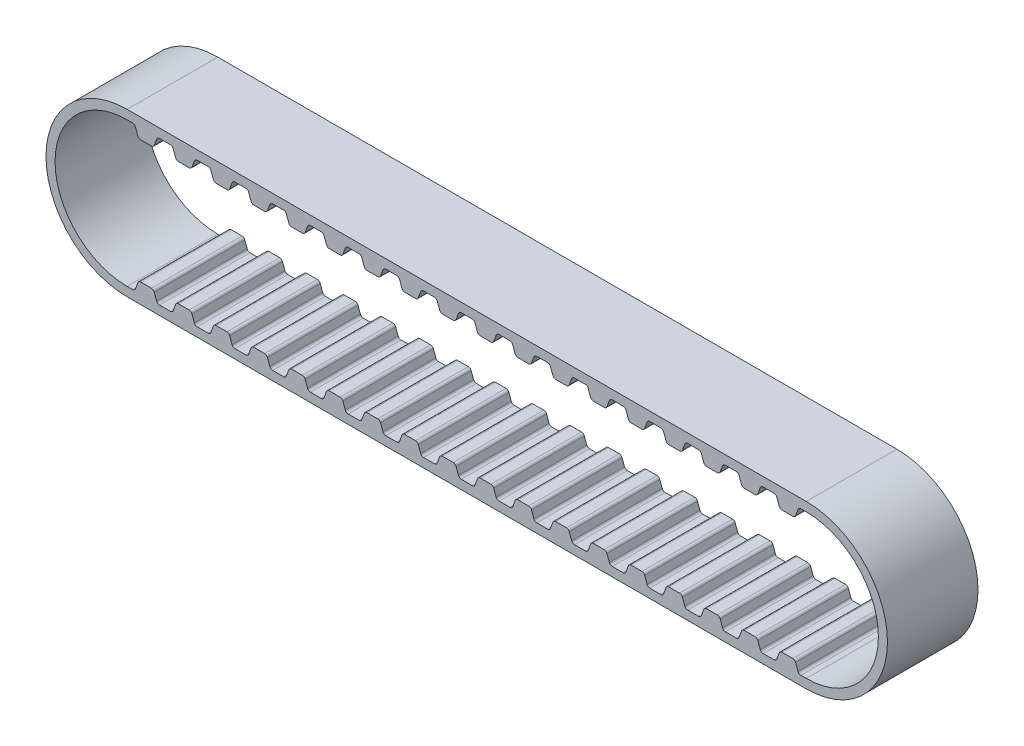
SolidWorks part; units mm, degrees
material "Gummi"
ref_plane "Ebene vorne" through (0, 0, 0) normal (0, 0, 1) x (1, 0, 0)
ref_plane "Ebene oben" through (0, 0, 0) normal (0, 1, 0) x (1, 0, 0)
ref_plane "Ebene rechts" through (0, 0, 0) normal (1, 0, 0) x (0, 0, -1)
sketch "Skizze1" plane through (0, 0, 0) normal (0, 0, 1) x (1, 0, 0)
  line L0 (0.7069, 1.1684) -> (0.5479, 0.7316)
  line L1 (0.36, 0.6) -> (0, 0.6)
  line L3 (0, 0) -> (45, 0)
  line L5 (21.9521, 0.7316) -> (21.7931, 1.1684)
  line L6 (11.9521, 0.7316) -> (11.7931, 1.1684)
  line L7 (11.6052, 1.3) -> (10.8948, 1.3)
  line L8 (10.7069, 1.1684) -> (10.5479, 0.7316)
  line L9 (10.36, 0.6) -> (9.64, 0.6)
  line L10 (9.4521, 0.7316) -> (9.2931, 1.1684)
  line L11 (9.1052, 1.3) -> (8.3948, 1.3)
  line L12 (8.2069, 1.1684) -> (8.0479, 0.7316)
  line L13 (7.86, 0.6) -> (7.14, 0.6)
  line L14 (6.9521, 0.7316) -> (6.7931, 1.1684)
  line L15 (6.6052, 1.3) -> (5.8948, 1.3)
  line L16 (5.7069, 1.1684) -> (5.5479, 0.7316)
  line L17 (5.36, 0.6) -> (4.64, 0.6)
  line L18 (4.4521, 0.7316) -> (4.2931, 1.1684)
  line L19 (4.1052, 1.3) -> (3.3948, 1.3)
  line L20 (3.2069, 1.1684) -> (3.0479, 0.7316)
  line L21 (2.86, 0.6) -> (2.14, 0.6)
  line L22 (1.9521, 0.7316) -> (1.7931, 1.1684)
  line L23 (1.6052, 1.3) -> (0.8948, 1.3)
  line L24 (21.6052, 1.3) -> (20.8948, 1.3)
  line L25 (20.7069, 1.1684) -> (20.5479, 0.7316)
  line L26 (20.36, 0.6) -> (19.64, 0.6)
  line L27 (19.4521, 0.7316) -> (19.2931, 1.1684)
  line L28 (19.1052, 1.3) -> (18.3948, 1.3)
  line L29 (18.2069, 1.1684) -> (18.0479, 0.7316)
  line L30 (17.86, 0.6) -> (17.14, 0.6)
  line L31 (16.9521, 0.7316) -> (16.7931, 1.1684)
  line L32 (16.6052, 1.3) -> (15.8948, 1.3)
  line L33 (15.7069, 1.1684) -> (15.5479, 0.7316)
  line L34 (15.36, 0.6) -> (14.64, 0.6)
  line L35 (14.4521, 0.7316) -> (14.2931, 1.1684)
  line L36 (14.1052, 1.3) -> (13.3948, 1.3)
  line L37 (13.2069, 1.1684) -> (13.0479, 0.7316)
  line L38 (12.86, 0.6) -> (12.14, 0.6)
  line L39 (31.9521, 0.7316) -> (31.7931, 1.1684)
  line L40 (31.6052, 1.3) -> (30.8948, 1.3)
  line L41 (30.7069, 1.1684) -> (30.5479, 0.7316)
  line L42 (30.36, 0.6) -> (29.64, 0.6)
  line L43 (29.4521, 0.7316) -> (29.2931, 1.1684)
  line L44 (29.1052, 1.3) -> (28.3948, 1.3)
  line L45 (28.2069, 1.1684) -> (28.0479, 0.7316)
  line L46 (27.86, 0.6) -> (27.14, 0.6)
  line L47 (26.9521, 0.7316) -> (26.7931, 1.1684)
  line L48 (26.6052, 1.3) -> (25.8948, 1.3)
  line L49 (25.7069, 1.1684) -> (25.5479, 0.7316)
  line L50 (25.36, 0.6) -> (24.64, 0.6)
  line L51 (24.4521, 0.7316) -> (24.2931, 1.1684)
  line L52 (24.1052, 1.3) -> (23.3948, 1.3)
  line L53 (23.2069, 1.1684) -> (23.0479, 0.7316)
  line L54 (22.86, 0.6) -> (22.14, 0.6)
  line L55 (41.9521, 0.7316) -> (41.7931, 1.1684)
  line L56 (41.6052, 1.3) -> (40.8948, 1.3)
  line L57 (40.7069, 1.1684) -> (40.5479, 0.7316)
  line L58 (40.36, 0.6) -> (39.64, 0.6)
  line L59 (39.4521, 0.7316) -> (39.2931, 1.1684)
  line L60 (39.1052, 1.3) -> (38.3948, 1.3)
  line L61 (38.2069, 1.1684) -> (38.0479, 0.7316)
  line L62 (37.86, 0.6) -> (37.14, 0.6)
  line L63 (36.9521, 0.7316) -> (36.7931, 1.1684)
  line L64 (36.6052, 1.3) -> (35.8948, 1.3)
  line L65 (35.7069, 1.1684) -> (35.5479, 0.7316)
  line L66 (35.36, 0.6) -> (34.64, 0.6)
  line L67 (34.4521, 0.7316) -> (34.2931, 1.1684)
  line L68 (34.1052, 1.3) -> (33.3948, 1.3)
  line L69 (33.2069, 1.1684) -> (33.0479, 0.7316)
  line L70 (32.86, 0.6) -> (32.14, 0.6)
  line L71 (44.4521, 0.7316) -> (44.2931, 1.1684)
  line L72 (44.1052, 1.3) -> (43.3948, 1.3)
  line L73 (43.2069, 1.1684) -> (43.0479, 0.7316)
  line L74 (42.86, 0.6) -> (42.14, 0.6)
  line L75 (44.64, 0.6) -> (45, 0.6)
  line L76 (45, 0.6) -> (45, 8.7132) construction
  line L80 (0, 10.76) -> (45, 10.76)
  line L153 (44.64, 10.16) -> (45, 10.16)
  line L154 (42.86, 10.16) -> (42.14, 10.16)
  line L155 (43.2069, 9.5916) -> (43.0479, 10.0284)
  line L156 (44.1052, 9.46) -> (43.3948, 9.46)
  line L157 (44.4521, 10.0284) -> (44.2931, 9.5916)
  line L158 (32.86, 10.16) -> (32.14, 10.16)
  line L159 (33.2069, 9.5916) -> (33.0479, 10.0284)
  line L160 (34.1052, 9.46) -> (33.3948, 9.46)
  line L161 (34.4521, 10.0284) -> (34.2931, 9.5916)
  line L162 (35.36, 10.16) -> (34.64, 10.16)
  line L163 (35.7069, 9.5916) -> (35.5479, 10.0284)
  line L164 (36.6052, 9.46) -> (35.8948, 9.46)
  line L165 (36.9521, 10.0284) -> (36.7931, 9.5916)
  line L166 (37.86, 10.16) -> (37.14, 10.16)
  line L167 (38.2069, 9.5916) -> (38.0479, 10.0284)
  line L168 (39.1052, 9.46) -> (38.3948, 9.46)
  line L169 (39.4521, 10.0284) -> (39.2931, 9.5916)
  line L170 (40.36, 10.16) -> (39.64, 10.16)
  line L171 (40.7069, 9.5916) -> (40.5479, 10.0284)
  line L172 (41.6052, 9.46) -> (40.8948, 9.46)
  line L173 (41.9521, 10.0284) -> (41.7931, 9.5916)
  line L174 (22.86, 10.16) -> (22.14, 10.16)
  line L175 (23.2069, 9.5916) -> (23.0479, 10.0284)
  line L176 (24.1052, 9.46) -> (23.3948, 9.46)
  line L177 (24.4521, 10.0284) -> (24.2931, 9.5916)
  line L178 (25.36, 10.16) -> (24.64, 10.16)
  line L179 (25.7069, 9.5916) -> (25.5479, 10.0284)
  line L180 (26.6052, 9.46) -> (25.8948, 9.46)
  line L181 (26.9521, 10.0284) -> (26.7931, 9.5916)
  line L182 (27.86, 10.16) -> (27.14, 10.16)
  line L183 (28.2069, 9.5916) -> (28.0479, 10.0284)
  line L184 (29.1052, 9.46) -> (28.3948, 9.46)
  line L185 (29.4521, 10.0284) -> (29.2931, 9.5916)
  line L186 (30.36, 10.16) -> (29.64, 10.16)
  line L187 (30.7069, 9.5916) -> (30.5479, 10.0284)
  line L188 (31.6052, 9.46) -> (30.8948, 9.46)
  line L189 (31.9521, 10.0284) -> (31.7931, 9.5916)
  line L190 (12.86, 10.16) -> (12.14, 10.16)
  line L191 (13.2069, 9.5916) -> (13.0479, 10.0284)
  line L192 (14.1052, 9.46) -> (13.3948, 9.46)
  line L193 (14.4521, 10.0284) -> (14.2931, 9.5916)
  line L194 (15.36, 10.16) -> (14.64, 10.16)
  line L195 (15.7069, 9.5916) -> (15.5479, 10.0284)
  line L196 (16.6052, 9.46) -> (15.8948, 9.46)
  line L197 (16.9521, 10.0284) -> (16.7931, 9.5916)
  line L198 (17.86, 10.16) -> (17.14, 10.16)
  line L199 (18.2069, 9.5916) -> (18.0479, 10.0284)
  line L200 (19.1052, 9.46) -> (18.3948, 9.46)
  line L201 (19.4521, 10.0284) -> (19.2931, 9.5916)
  line L202 (20.36, 10.16) -> (19.64, 10.16)
  line L203 (20.7069, 9.5916) -> (20.5479, 10.0284)
  line L204 (21.6052, 9.46) -> (20.8948, 9.46)
  line L205 (1.6052, 9.46) -> (0.8948, 9.46)
  line L206 (1.9521, 10.0284) -> (1.7931, 9.5916)
  line L207 (2.86, 10.16) -> (2.14, 10.16)
  line L208 (3.2069, 9.5916) -> (3.0479, 10.0284)
  line L209 (4.1052, 9.46) -> (3.3948, 9.46)
  line L210 (4.4521, 10.0284) -> (4.2931, 9.5916)
  line L211 (5.36, 10.16) -> (4.64, 10.16)
  line L212 (5.7069, 9.5916) -> (5.5479, 10.0284)
  line L213 (6.6052, 9.46) -> (5.8948, 9.46)
  line L214 (6.9521, 10.0284) -> (6.7931, 9.5916)
  line L215 (7.86, 10.16) -> (7.14, 10.16)
  line L216 (8.2069, 9.5916) -> (8.0479, 10.0284)
  line L217 (9.1052, 9.46) -> (8.3948, 9.46)
  line L218 (9.4521, 10.0284) -> (9.2931, 9.5916)
  line L219 (10.36, 10.16) -> (9.64, 10.16)
  line L220 (10.7069, 9.5916) -> (10.5479, 10.0284)
  line L221 (11.6052, 9.46) -> (10.8948, 9.46)
  line L222 (11.9521, 10.0284) -> (11.7931, 9.5916)
  line L223 (21.9521, 10.0284) -> (21.7931, 9.5916)
  line L226 (0.36, 10.16) -> (0, 10.16)
  line L227 (0.7069, 9.5916) -> (0.5479, 10.0284)
  line L228 (45, 8.7132) -> (45, 14.9063) construction
  line L229 (0, 0) -> (0, 10.76) construction
  arc A0 (0.5479, 0.7316) -> (0.36, 0.6) centre (0.36, 0.8) cw
  arc A1 (12.14, 0.6) -> (11.9521, 0.7316) centre (12.14, 0.8) cw
  arc A2 (11.7931, 1.1684) -> (11.6052, 1.3) centre (11.6052, 1.1) ccw
  arc A3 (10.8948, 1.3) -> (10.7069, 1.1684) centre (10.8948, 1.1) ccw
  arc A4 (10.5479, 0.7316) -> (10.36, 0.6) centre (10.36, 0.8) cw
  arc A5 (9.64, 0.6) -> (9.4521, 0.7316) centre (9.64, 0.8) cw
  arc A6 (9.2931, 1.1684) -> (9.1052, 1.3) centre (9.1052, 1.1) ccw
  arc A7 (8.3948, 1.3) -> (8.2069, 1.1684) centre (8.3948, 1.1) ccw
  arc A8 (8.0479, 0.7316) -> (7.86, 0.6) centre (7.86, 0.8) cw
  arc A9 (7.14, 0.6) -> (6.9521, 0.7316) centre (7.14, 0.8) cw
  arc A10 (6.7931, 1.1684) -> (6.6052, 1.3) centre (6.6052, 1.1) ccw
  arc A11 (5.8948, 1.3) -> (5.7069, 1.1684) centre (5.8948, 1.1) ccw
  arc A12 (5.5479, 0.7316) -> (5.36, 0.6) centre (5.36, 0.8) cw
  arc A13 (4.64, 0.6) -> (4.4521, 0.7316) centre (4.64, 0.8) cw
  arc A14 (4.2931, 1.1684) -> (4.1052, 1.3) centre (4.1052, 1.1) ccw
  arc A15 (3.3948, 1.3) -> (3.2069, 1.1684) centre (3.3948, 1.1) ccw
  arc A16 (3.0479, 0.7316) -> (2.86, 0.6) centre (2.86, 0.8) cw
  arc A17 (2.14, 0.6) -> (1.9521, 0.7316) centre (2.14, 0.8) cw
  arc A18 (1.7931, 1.1684) -> (1.6052, 1.3) centre (1.6052, 1.1) ccw
  arc A19 (0.8948, 1.3) -> (0.7069, 1.1684) centre (0.8948, 1.1) ccw
  arc A20 (22.14, 0.6) -> (21.9521, 0.7316) centre (22.14, 0.8) cw
  arc A21 (21.7931, 1.1684) -> (21.6052, 1.3) centre (21.6052, 1.1) ccw
  arc A22 (20.8948, 1.3) -> (20.7069, 1.1684) centre (20.8948, 1.1) ccw
  arc A23 (20.5479, 0.7316) -> (20.36, 0.6) centre (20.36, 0.8) cw
  arc A24 (19.64, 0.6) -> (19.4521, 0.7316) centre (19.64, 0.8) cw
  arc A25 (19.2931, 1.1684) -> (19.1052, 1.3) centre (19.1052, 1.1) ccw
  arc A26 (18.3948, 1.3) -> (18.2069, 1.1684) centre (18.3948, 1.1) ccw
  arc A27 (18.0479, 0.7316) -> (17.86, 0.6) centre (17.86, 0.8) cw
  arc A28 (17.14, 0.6) -> (16.9521, 0.7316) centre (17.14, 0.8) cw
  arc A29 (16.7931, 1.1684) -> (16.6052, 1.3) centre (16.6052, 1.1) ccw
  arc A30 (15.8948, 1.3) -> (15.7069, 1.1684) centre (15.8948, 1.1) ccw
  arc A31 (15.5479, 0.7316) -> (15.36, 0.6) centre (15.36, 0.8) cw
  arc A32 (14.64, 0.6) -> (14.4521, 0.7316) centre (14.64, 0.8) cw
  arc A33 (14.2931, 1.1684) -> (14.1052, 1.3) centre (14.1052, 1.1) ccw
  arc A34 (13.3948, 1.3) -> (13.2069, 1.1684) centre (13.3948, 1.1) ccw
  arc A35 (13.0479, 0.7316) -> (12.86, 0.6) centre (12.86, 0.8) cw
  arc A36 (32.14, 0.6) -> (31.9521, 0.7316) centre (32.14, 0.8) cw
  arc A37 (31.7931, 1.1684) -> (31.6052, 1.3) centre (31.6052, 1.1) ccw
  arc A38 (30.8948, 1.3) -> (30.7069, 1.1684) centre (30.8948, 1.1) ccw
  arc A39 (30.5479, 0.7316) -> (30.36, 0.6) centre (30.36, 0.8) cw
  arc A40 (29.64, 0.6) -> (29.4521, 0.7316) centre (29.64, 0.8) cw
  arc A41 (29.2931, 1.1684) -> (29.1052, 1.3) centre (29.1052, 1.1) ccw
  arc A42 (28.3948, 1.3) -> (28.2069, 1.1684) centre (28.3948, 1.1) ccw
  arc A43 (28.0479, 0.7316) -> (27.86, 0.6) centre (27.86, 0.8) cw
  arc A44 (27.14, 0.6) -> (26.9521, 0.7316) centre (27.14, 0.8) cw
  arc A45 (26.7931, 1.1684) -> (26.6052, 1.3) centre (26.6052, 1.1) ccw
  arc A46 (25.8948, 1.3) -> (25.7069, 1.1684) centre (25.8948, 1.1) ccw
  arc A47 (25.5479, 0.7316) -> (25.36, 0.6) centre (25.36, 0.8) cw
  arc A48 (24.64, 0.6) -> (24.4521, 0.7316) centre (24.64, 0.8) cw
  arc A49 (24.2931, 1.1684) -> (24.1052, 1.3) centre (24.1052, 1.1) ccw
  arc A50 (23.3948, 1.3) -> (23.2069, 1.1684) centre (23.3948, 1.1) ccw
  arc A51 (23.0479, 0.7316) -> (22.86, 0.6) centre (22.86, 0.8) cw
  arc A52 (42.14, 0.6) -> (41.9521, 0.7316) centre (42.14, 0.8) cw
  arc A53 (41.7931, 1.1684) -> (41.6052, 1.3) centre (41.6052, 1.1) ccw
  arc A54 (40.8948, 1.3) -> (40.7069, 1.1684) centre (40.8948, 1.1) ccw
  arc A55 (40.5479, 0.7316) -> (40.36, 0.6) centre (40.36, 0.8) cw
  arc A56 (39.64, 0.6) -> (39.4521, 0.7316) centre (39.64, 0.8) cw
  arc A57 (39.2931, 1.1684) -> (39.1052, 1.3) centre (39.1052, 1.1) ccw
  arc A58 (38.3948, 1.3) -> (38.2069, 1.1684) centre (38.3948, 1.1) ccw
  arc A59 (38.0479, 0.7316) -> (37.86, 0.6) centre (37.86, 0.8) cw
  arc A60 (37.14, 0.6) -> (36.9521, 0.7316) centre (37.14, 0.8) cw
  arc A61 (36.7931, 1.1684) -> (36.6052, 1.3) centre (36.6052, 1.1) ccw
  arc A62 (35.8948, 1.3) -> (35.7069, 1.1684) centre (35.8948, 1.1) ccw
  arc A63 (35.5479, 0.7316) -> (35.36, 0.6) centre (35.36, 0.8) cw
  arc A64 (34.64, 0.6) -> (34.4521, 0.7316) centre (34.64, 0.8) cw
  arc A65 (34.2931, 1.1684) -> (34.1052, 1.3) centre (34.1052, 1.1) ccw
  arc A66 (33.3948, 1.3) -> (33.2069, 1.1684) centre (33.3948, 1.1) ccw
  arc A67 (33.0479, 0.7316) -> (32.86, 0.6) centre (32.86, 0.8) cw
  arc A68 (44.64, 0.6) -> (44.4521, 0.7316) centre (44.64, 0.8) cw
  arc A69 (44.2931, 1.1684) -> (44.1052, 1.3) centre (44.1052, 1.1) ccw
  arc A70 (43.3948, 1.3) -> (43.2069, 1.1684) centre (43.3948, 1.1) ccw
  arc A71 (43.0479, 0.7316) -> (42.86, 0.6) centre (42.86, 0.8) cw
  arc A73 (45, 0) -> (45, 10.76) centre (45, 5.38) ccw
  arc A74 (45, 0.6) -> (45, 10.16) centre (45, 5.38) ccw
  arc A147 (43.0479, 10.0284) -> (42.86, 10.16) centre (42.86, 9.96) ccw
  arc A148 (43.3948, 9.46) -> (43.2069, 9.5916) centre (43.3948, 9.66) cw
  arc A149 (44.2931, 9.5916) -> (44.1052, 9.46) centre (44.1052, 9.66) cw
  arc A150 (44.64, 10.16) -> (44.4521, 10.0284) centre (44.64, 9.96) ccw
  arc A151 (33.0479, 10.0284) -> (32.86, 10.16) centre (32.86, 9.96) ccw
  arc A152 (33.3948, 9.46) -> (33.2069, 9.5916) centre (33.3948, 9.66) cw
  arc A153 (34.2931, 9.5916) -> (34.1052, 9.46) centre (34.1052, 9.66) cw
  arc A154 (34.64, 10.16) -> (34.4521, 10.0284) centre (34.64, 9.96) ccw
  arc A155 (35.5479, 10.0284) -> (35.36, 10.16) centre (35.36, 9.96) ccw
  arc A156 (35.8948, 9.46) -> (35.7069, 9.5916) centre (35.8948, 9.66) cw
  arc A157 (36.7931, 9.5916) -> (36.6052, 9.46) centre (36.6052, 9.66) cw
  arc A158 (37.14, 10.16) -> (36.9521, 10.0284) centre (37.14, 9.96) ccw
  arc A159 (38.0479, 10.0284) -> (37.86, 10.16) centre (37.86, 9.96) ccw
  arc A160 (38.3948, 9.46) -> (38.2069, 9.5916) centre (38.3948, 9.66) cw
  arc A161 (39.2931, 9.5916) -> (39.1052, 9.46) centre (39.1052, 9.66) cw
  arc A162 (39.64, 10.16) -> (39.4521, 10.0284) centre (39.64, 9.96) ccw
  arc A163 (40.5479, 10.0284) -> (40.36, 10.16) centre (40.36, 9.96) ccw
  arc A164 (40.8948, 9.46) -> (40.7069, 9.5916) centre (40.8948, 9.66) cw
  arc A165 (41.7931, 9.5916) -> (41.6052, 9.46) centre (41.6052, 9.66) cw
  arc A166 (42.14, 10.16) -> (41.9521, 10.0284) centre (42.14, 9.96) ccw
  arc A167 (23.0479, 10.0284) -> (22.86, 10.16) centre (22.86, 9.96) ccw
  arc A168 (23.3948, 9.46) -> (23.2069, 9.5916) centre (23.3948, 9.66) cw
  arc A169 (24.2931, 9.5916) -> (24.1052, 9.46) centre (24.1052, 9.66) cw
  arc A170 (24.64, 10.16) -> (24.4521, 10.0284) centre (24.64, 9.96) ccw
  arc A171 (25.5479, 10.0284) -> (25.36, 10.16) centre (25.36, 9.96) ccw
  arc A172 (25.8948, 9.46) -> (25.7069, 9.5916) centre (25.8948, 9.66) cw
  arc A173 (26.7931, 9.5916) -> (26.6052, 9.46) centre (26.6052, 9.66) cw
  arc A174 (27.14, 10.16) -> (26.9521, 10.0284) centre (27.14, 9.96) ccw
  arc A175 (28.0479, 10.0284) -> (27.86, 10.16) centre (27.86, 9.96) ccw
  arc A176 (28.3948, 9.46) -> (28.2069, 9.5916) centre (28.3948, 9.66) cw
  arc A177 (29.2931, 9.5916) -> (29.1052, 9.46) centre (29.1052, 9.66) cw
  arc A178 (29.64, 10.16) -> (29.4521, 10.0284) centre (29.64, 9.96) ccw
  arc A179 (30.5479, 10.0284) -> (30.36, 10.16) centre (30.36, 9.96) ccw
  arc A180 (30.8948, 9.46) -> (30.7069, 9.5916) centre (30.8948, 9.66) cw
  arc A181 (31.7931, 9.5916) -> (31.6052, 9.46) centre (31.6052, 9.66) cw
  arc A182 (32.14, 10.16) -> (31.9521, 10.0284) centre (32.14, 9.96) ccw
  arc A183 (13.0479, 10.0284) -> (12.86, 10.16) centre (12.86, 9.96) ccw
  arc A184 (13.3948, 9.46) -> (13.2069, 9.5916) centre (13.3948, 9.66) cw
  arc A185 (14.2931, 9.5916) -> (14.1052, 9.46) centre (14.1052, 9.66) cw
  arc A186 (14.64, 10.16) -> (14.4521, 10.0284) centre (14.64, 9.96) ccw
  arc A187 (15.5479, 10.0284) -> (15.36, 10.16) centre (15.36, 9.96) ccw
  arc A188 (15.8948, 9.46) -> (15.7069, 9.5916) centre (15.8948, 9.66) cw
  arc A189 (16.7931, 9.5916) -> (16.6052, 9.46) centre (16.6052, 9.66) cw
  arc A190 (17.14, 10.16) -> (16.9521, 10.0284) centre (17.14, 9.96) ccw
  arc A191 (18.0479, 10.0284) -> (17.86, 10.16) centre (17.86, 9.96) ccw
  arc A192 (18.3948, 9.46) -> (18.2069, 9.5916) centre (18.3948, 9.66) cw
  arc A193 (19.2931, 9.5916) -> (19.1052, 9.46) centre (19.1052, 9.66) cw
  arc A194 (19.64, 10.16) -> (19.4521, 10.0284) centre (19.64, 9.96) ccw
  arc A195 (20.5479, 10.0284) -> (20.36, 10.16) centre (20.36, 9.96) ccw
  arc A196 (20.8948, 9.46) -> (20.7069, 9.5916) centre (20.8948, 9.66) cw
  arc A197 (21.7931, 9.5916) -> (21.6052, 9.46) centre (21.6052, 9.66) cw
  arc A198 (22.14, 10.16) -> (21.9521, 10.0284) centre (22.14, 9.96) ccw
  arc A199 (0.8948, 9.46) -> (0.7069, 9.5916) centre (0.8948, 9.66) cw
  arc A200 (1.7931, 9.5916) -> (1.6052, 9.46) centre (1.6052, 9.66) cw
  arc A201 (2.14, 10.16) -> (1.9521, 10.0284) centre (2.14, 9.96) ccw
  arc A202 (3.0479, 10.0284) -> (2.86, 10.16) centre (2.86, 9.96) ccw
  arc A203 (3.3948, 9.46) -> (3.2069, 9.5916) centre (3.3948, 9.66) cw
  arc A204 (4.2931, 9.5916) -> (4.1052, 9.46) centre (4.1052, 9.66) cw
  arc A205 (4.64, 10.16) -> (4.4521, 10.0284) centre (4.64, 9.96) ccw
  arc A206 (5.5479, 10.0284) -> (5.36, 10.16) centre (5.36, 9.96) ccw
  arc A207 (5.8948, 9.46) -> (5.7069, 9.5916) centre (5.8948, 9.66) cw
  arc A208 (6.7931, 9.5916) -> (6.6052, 9.46) centre (6.6052, 9.66) cw
  arc A209 (7.14, 10.16) -> (6.9521, 10.0284) centre (7.14, 9.96) ccw
  arc A210 (8.0479, 10.0284) -> (7.86, 10.16) centre (7.86, 9.96) ccw
  arc A211 (8.3948, 9.46) -> (8.2069, 9.5916) centre (8.3948, 9.66) cw
  arc A212 (9.2931, 9.5916) -> (9.1052, 9.46) centre (9.1052, 9.66) cw
  arc A213 (9.64, 10.16) -> (9.4521, 10.0284) centre (9.64, 9.96) ccw
  arc A214 (10.5479, 10.0284) -> (10.36, 10.16) centre (10.36, 9.96) ccw
  arc A215 (10.8948, 9.46) -> (10.7069, 9.5916) centre (10.8948, 9.66) cw
  arc A216 (11.7931, 9.5916) -> (11.6052, 9.46) centre (11.6052, 9.66) cw
  arc A217 (12.14, 10.16) -> (11.9521, 10.0284) centre (12.14, 9.96) ccw
  arc A218 (0.5479, 10.0284) -> (0.36, 10.16) centre (0.36, 9.96) ccw
  arc A223 (0, 10.16) -> (0, 0.6) centre (0, 5.38) ccw
  arc A224 (0, 10.76) -> (0, 0) centre (0, 5.38) ccw
extrude "Aufsatz-Linear austragen1" add sketch "Skizze1" against normal blind 6
